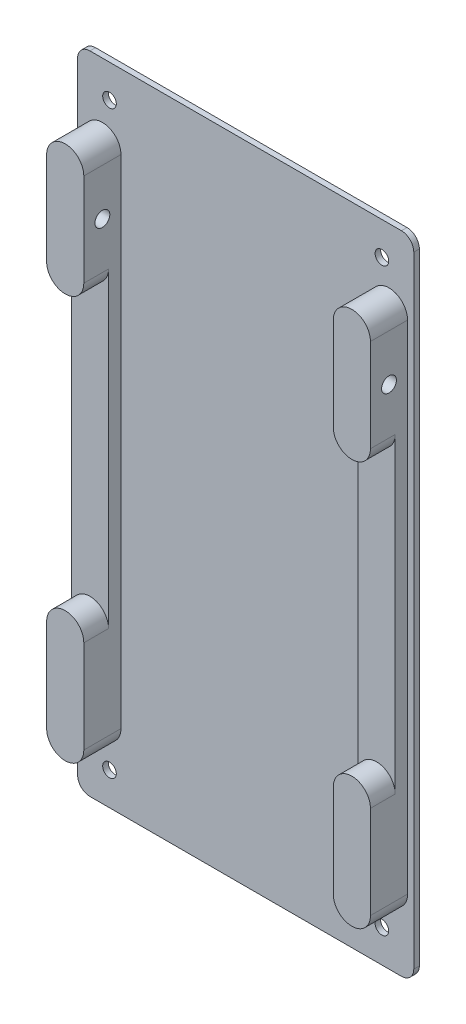
SolidWorks part; units mm, degrees
ref_plane "Přední rovina" through (0, 0, 0) normal (0, 0, 1) x (1, 0, 0)
ref_plane "Horní rovina" through (0, 0, 0) normal (0, 1, 0) x (1, 0, 0)
ref_plane "Pravá rovina" through (0, 0, 0) normal (1, 0, 0) x (0, 0, -1)
sketch "Skica1" plane through (0, 0, 0) normal (0, 0, 1) x (1, 0, 0)
  line L1 (0, 0) -> (54.3, 0)
  line L2 (0, 0) -> (0, 104.3)
  line L3 (0, 104.3) -> (54.3, 104.3)
  line L4 (54.3, 0) -> (54.3, 104.3)
  dimension "D1" = 104.3
  dimension "D2" = 54.3
extrude "Přidat vysunutím1" add sketch "Skica1" along normal blind 0.9
fillet "Zaoblit1" radius 2 4 edges at (0, 0, 0.45) (54.3, 0, 0.45) (0, 104.3, 0.45) (54.3, 104.3, 0.45)
sketch "Skica2" plane through (0, 0, 0.9) normal (0, 0, 1) x (1, 0, 0)
  line L0 (52.3, 104.3) -> (2, 104.3) construction
  line L1 (0, 102.3) -> (0, 2) construction
  line L2 (54.3, 2) -> (54.3, 102.3) construction
  line L3 (2, 0) -> (52.3, 0) construction
  circle A0 centre (5.15, 99) radius 1.1
  circle A1 centre (49.15, 99) radius 1.1
  circle A2 centre (5.15, 5.3) radius 1.1
  circle A3 centre (49.15, 5.3) radius 1.1
  dimension "D1" = 2.2
  dimension "D2" = 2.2
  dimension "D3" = 2.2
  dimension "D4" = 2.2
  dimension "D5" = 5.3
  dimension "D6" = 5.15
  dimension "D7" = 5.15
  dimension "D8" = 5.3
extrude "Odebrat vysunutím1" cut sketch "Skica2" against normal blind 0.9
sketch "Skica3" plane through (0, 0, 0.9) normal (0, 0, 1) x (1, 0, 0)
  line L0 (4, 92.3) -> (4, 77.3) construction
  line L1 (7, 92.3) -> (7, 77.3)
  line L2 (1, 92.3) -> (1, 77.3)
  line L3 (50.3, 92.3) -> (50.3, 77.3) construction
  line L4 (53.3, 92.3) -> (53.3, 77.3)
  line L5 (47.3, 92.3) -> (47.3, 77.3)
  line L6 (4, 27) -> (4, 12) construction
  line L7 (7, 27) -> (7, 12)
  line L8 (1, 27) -> (1, 12)
  line L9 (50.3, 27) -> (50.3, 12) construction
  line L10 (53.3, 27) -> (53.3, 12)
  line L11 (47.3, 27) -> (47.3, 12)
  line L12 (0, 102.3) -> (0, 2) construction
  line L13 (54.3, 2) -> (54.3, 102.3) construction
  line L14 (52.3, 104.3) -> (2, 104.3) construction
  line L15 (2, 0) -> (52.3, 0) construction
  arc A0 (7, 92.3) -> (1, 92.3) centre (4, 92.3) ccw
  arc A1 (1, 77.3) -> (7, 77.3) centre (4, 77.3) ccw
  arc A2 (53.3, 92.3) -> (47.3, 92.3) centre (50.3, 92.3) ccw
  arc A3 (47.3, 77.3) -> (53.3, 77.3) centre (50.3, 77.3) ccw
  arc A4 (7, 27) -> (1, 27) centre (4, 27) ccw
  arc A5 (1, 12) -> (7, 12) centre (4, 12) ccw
  arc A6 (53.3, 27) -> (47.3, 27) centre (50.3, 27) ccw
  arc A7 (47.3, 12) -> (53.3, 12) centre (50.3, 12) ccw
  point P2 (4, 84.8)
  point P7 (50.3, 84.8)
  point P14 (4, 19.5)
  point P21 (50.3, 19.5)
  point P28 (4, 30)
  point P29 (4, 9)
  point P30 (50.3, 30)
  point P31 (50.3, 9)
  point P32 (50.3, 74.3)
  point P33 (50.3, 95.3)
  point P34 (4, 95.3)
  point P35 (4, 74.3)
  dimension "D1" = 6
  dimension "D2" = 6
  dimension "D3" = 6
  dimension "D4" = 6
  dimension "D5" = 21
  dimension "D6" = 21
  dimension "D7" = 21
  dimension "D8" = 21
  dimension "D9" = 1
  dimension "D10" = 1
  dimension "D11" = 9
  dimension "D12" = 9
extrude "Přidat vysunutím2" add sketch "Skica3" along normal blind 6
sketch "Skica4" plane through (53.3, 0, 0) normal (1, 0, 0) x (0, 0, -1)
  line L0 (-6.9, 92.3) -> (-0.9, 77.3) construction
  circle A0 centre (-3.9, 84.8) radius 1.2
  dimension "D1" = 2.4
extrude "Odebrat vysunutím2" cut sketch "Skica4" against normal through all and the other way through all
sketch "Skica5" plane through (0, 0, 0.9) normal (0, 0, 1) x (1, 0, 0)
  line L1 (1, 77.3) -> (7, 77.3)
  line L2 (1, 77.3) -> (1, 27)
  line L3 (1, 27) -> (7, 27)
  line L4 (7, 77.3) -> (7, 27)
  line L5 (53.3, 77.3) -> (47.3, 77.3)
  line L6 (53.3, 77.3) -> (53.3, 27)
  line L7 (53.3, 27) -> (47.3, 27)
  line L8 (47.3, 77.3) -> (47.3, 27)
extrude "Přidat vysunutím3" add sketch "Skica5" along normal blind 2
